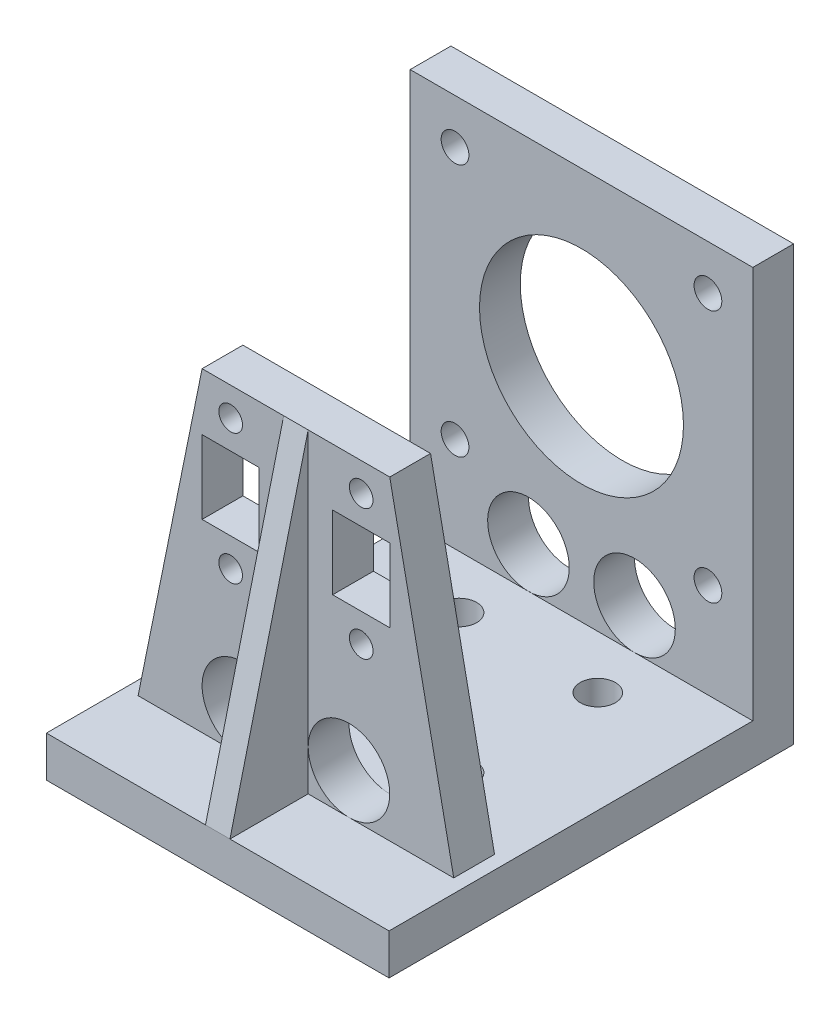
SolidWorks part; units mm, degrees
material "ABS"
ref_plane "Front Plane" through (0, 0, 0) normal (0, 0, 1) x (1, 0, 0)
ref_plane "Top Plane" through (0, 0, 0) normal (0, 1, 0) x (1, 0, 0)
ref_plane "Right Plane" through (0, 0, 0) normal (1, 0, 0) x (0, 0, -1)
sketch "Mouting Mount Sketch" plane through (0, 0, 0) normal (0, 0, 1) x (1, 0, 0)
  line L1 (25, -55) -> (-25, -55)
  line L2 (25, -55) -> (25, 0)
  line L3 (25, 0) -> (-25, 0)
  line L4 (-25, -55) -> (-25, 0)
  line L5 (25, -55) -> (-25, 0) construction
  line L6 (25, 0) -> (-25, -55) construction
  circle A0 centre (0, 0) radius 10
  point P3 (0, -27.5)
  dimension "D1" = 20
  dimension "D2" = 50
  dimension "D3" = 55
extrude "Motor Mount Solid" add sketch "Mouting Mount Sketch" along normal mid plane 15 contours A0 L3 L4 L1 L2
sketch "Encoder Distance Sketch" plane through (0, -55, 0) normal (0, -1, 0) x (1, 0, 0)
  line L0 (25, 7.5) -> (25, -7.5) construction
  line L1 (-25, 7.5) -> (25, 7.5)
  line L2 (-25, 7.5) -> (-25, 37.5)
  line L3 (-25, 37.5) -> (25, 37.5)
  line L4 (25, 7.5) -> (25, 37.5)
  line L5 (-25, -7.5) -> (25, -7.5) construction
  line L6 (-25, -7.5) -> (-25, 42.5) construction
  line L7 (-25, 42.5) -> (25, 42.5) construction
  line L8 (25, -7.5) -> (25, 42.5) construction
  line M9 (-25, -7.5) -> (25, -7.5)
  line M10 (25, -7.5) -> (25, 7.5)
  line M11 (25, 7.5) -> (-25, 7.5)
  line M12 (-25, 7.5) -> (-25, -7.5)
  dimension "D1" = 30
  dimension "D2" = 5
extrude "Encoder Distance Solid" add sketch "Encoder Distance Sketch" along normal blind 5 contours M12 M9 M10 M11 | L4 L3 L2 M11 | L3 L8 L7 L6
sketch "Encoder Mount Sketch" plane through (0, 0, 37.5) normal (0, 0, 1) x (1, 0, 0)
  line L0 (-25, -60) -> (-25, -55)
  line L1 (-8, -8) -> (8, -8) construction
  line L2 (-8, -8) -> (-8, 8) construction
  line L3 (-8, 8) -> (8, 8) construction
  line L4 (8, -8) -> (8, 8) construction
  line L5 (-8, -8) -> (8, 8) construction
  line L6 (-8, 8) -> (8, -8) construction
  line L7 (-11.5, -11.5) -> (11.5, -11.5) construction
  line L8 (-11.5, -11.5) -> (-11.5, 11.5) construction
  line L9 (-11.5, 11.5) -> (11.5, 11.5)
  line L10 (11.5, -11.5) -> (11.5, 11.5) construction
  line L11 (-11.5, -11.5) -> (11.5, 11.5) construction
  line L12 (-11.5, 11.5) -> (11.5, -11.5) construction
  line L13 (-11.5, 4.5) -> (-4.5, 4.5)
  line L14 (-11.5, 4.5) -> (-11.5, -4.5)
  line L15 (-11.5, -4.5) -> (-4.5, -4.5)
  line L16 (-4.5, 4.5) -> (-4.5, -4.5)
  line L17 (-11.5, 4.5) -> (-4.5, -4.5) construction
  line L18 (-11.5, -4.5) -> (-4.5, 4.5) construction
  line L19 (4.5, 4.5) -> (11.5, 4.5)
  line L20 (4.5, 4.5) -> (4.5, -4.5)
  line L21 (4.5, -4.5) -> (11.5, -4.5)
  line L22 (11.5, 4.5) -> (11.5, -4.5)
  line L23 (4.5, 4.5) -> (11.5, -4.5) construction
  line L24 (4.5, -4.5) -> (11.5, 4.5) construction
  line L25 (-25, -55) -> (-11.5, 11.5)
  line L26 (-25, -60) -> (25, -60)
  line L27 (25, -60) -> (25, -55)
  line L28 (25, -55) -> (11.5, 11.5)
  circle A0 centre (-8, 8) radius 1.45
  circle A1 centre (8, 8) radius 1.45
  circle A2 centre (-8, -8) radius 1.45
  circle A3 centre (8, -8) radius 1.45
  circle A4 centre (8, 8) radius 3.5 construction
  circle A5 centre (-8, 8) radius 3.5 construction
  circle A6 centre (-8, -8) radius 3.5 construction
  circle A7 centre (8, -8) radius 3.5 construction
  point P0 (0, 0)
  point P14 (0, 0)
  point P19 (-8, 0)
  point P24 (8, 0)
  dimension "D2" = 2.9
  dimension "D3" = 7
  dimension "D1" = 16
extrude "Encoder Mount Solid" add sketch "Encoder Mount Sketch" along normal blind 5
sketch "Motor Clamp Mounting Holes Sketch" plane through (0, 0, 0) normal (0, 1, 0) x (1, 0, 0)
  line L0 (-15, 0) -> (15, 0) construction
  circle A0 centre (-15, 0) radius 1.45
  circle A1 centre (15, 0) radius 1.45
  point P4 (0, 0)
  dimension "D2" = 2.9
  dimension "D1" = 30
extrude "Motor Clamp Mounting Holes Cut" cut sketch "Motor Clamp Mounting Holes Sketch" against normal through all both and the other way through all
sketch "Gusset Plate Sketch" plane through (0, 0, 42.5) normal (0, 0, 1) x (1, 0, 0)
  line L1 (-25, -55) -> (25, -55)
  line L2 (-25, -55) -> (-25, -60)
  line L3 (-25, -60) -> (25, -60)
  line L4 (25, -55) -> (25, -60)
extrude "Gusset Plate Solid" add sketch "Gusset Plate Sketch" along normal blind 16.5
sketch "Gusset Sketch" plane through (0, 0, 0) normal (1, 0, 0) x (0, 0, -1)
  line L0 (-42.5, 11.5) -> (-59, -55)
  line L1 (-59, -55) -> (-42.5, -55)
  line L2 (-42.5, -55) -> (-42.5, 11.5)
extrude "Gusset Solid" add sketch "Gusset Sketch" along normal mid plane 3
sketch "Mounting Plate Sketch" plane through (0, -55, 0) normal (0, 1, 0) x (1, 0, 0)
  line L0 (25, -7.5) -> (25, -37.5) construction
  line L1 (-25, -59) -> (25, -59)
  line L2 (-25, -59) -> (-25, 33)
  line L3 (-25, 33) -> (25, 33)
  line L4 (25, -59) -> (25, 33)
  line L5 (-19, -53) -> (19, -53) construction
  line L6 (-19, 27) -> (19, 27) construction
  circle A0 centre (-19, -53) radius 2.65
  circle A1 centre (19, -53) radius 6 construction
  circle A2 centre (19, -53) radius 2.65
  circle A3 centre (-19, -53) radius 6 construction
  circle A4 centre (-19, 27) radius 6 construction
  circle A5 centre (19, 27) radius 6 construction
  circle A6 centre (-19, 27) radius 2.65
  circle A7 centre (19, 27) radius 2.65
  point P10 (0, -53)
  point P18 (0, 27)
  dimension "D1" = 12
  dimension "D2" = 5.3
  dimension "D3" = 80
extrude "Mounting Plate Solid" add sketch "Mounting Plate Sketch" against normal up to surface (5 mm away) up to face at (-16.45, -60, 0)
sketch "Mounting Hole Sketch" plane through (0, -55, 0) normal (0, 1, 0) x (1, 0, 0)
  line L0 (25, 33) -> (25, -59) construction
  line L3 (25, -13) -> (-25, -13) construction
  line L4 (-25, -37.5) -> (-25, -7.5) construction
  circle A0 centre (-19, 27) radius 2.65
  circle A1 centre (19, 27) radius 2.65
  circle A3 centre (19, -53) radius 2.65
  circle A4 centre (-19, -53) radius 2.65
  circle A5 centre (-19, 27) radius 2.65 construction
extrude "Mounting Holes Cut" cut sketch "Mounting Hole Sketch" against normal through all both and the other way through all contours A3 | A4 | A1 | A0
sketch "Mounting Plate Trim Sketch" plane through (0, -55, 0) normal (0, 1, 0) x (1, 0, 0)
  line L1 (-25, 33) -> (25, 33)
  line L2 (-25, 33) -> (-25, 7.5)
  line L3 (-25, 7.5) -> (25, 7.5)
  line L4 (25, 33) -> (25, 7.5)
  line L5 (-25, -7.5) -> (25, -7.5)
  line L6 (-25, -7.5) -> (-25, -37.5)
  line L7 (-25, -37.5) -> (25, -37.5)
  line L8 (25, -7.5) -> (25, -37.5)
  line L9 (1.5, -42.5) -> (25, -42.5)
  line L10 (1.5, -42.5) -> (1.5, -59)
  line L11 (1.5, -59) -> (25, -59)
  line L12 (25, -42.5) -> (25, -59)
  line L13 (-1.5, -42.5) -> (-25, -42.5)
  line L14 (-1.5, -42.5) -> (-1.5, -59)
  line L15 (-1.5, -59) -> (-25, -59)
  line L16 (-25, -42.5) -> (-25, -59)
extrude "Mounting Plate Trim Cut" cut sketch "Mounting Plate Trim Sketch" against normal blind 2
sketch "Sketch2" plane through (0, 0, -7.5) normal (0, 0, -1) x (-1, 0, 0)
  line L1 (-21, -27.1363) -> (21, -27.1363)
  line L2 (-21, -27.1363) -> (-21, 27.1363)
  line L3 (-21, 27.1363) -> (21, 27.1363)
  line L4 (21, -27.1363) -> (21, 27.1363)
  line L5 (-21, -27.1363) -> (21, 27.1363) construction
  line L6 (-21, 27.1363) -> (21, -27.1363) construction
  line L7 (25, 60) -> (-25, 60)
  line L8 (25, 60) -> (25, -60)
  line L9 (25, -60) -> (-25, -60)
  line L10 (-25, 60) -> (-25, -60)
  line L11 (25, 60) -> (-25, -60) construction
  line L12 (25, -60) -> (-25, 60) construction
  point P0 (0, 0)
  point P7 (0, 0)
  dimension "D1" = 42
  dimension "D2" = 27.1363
extrude "Cut-Extrude1" cut sketch "Sketch2" against normal through all both and the other way through all
sketch "Sketch3" plane through (0, -27.1363, 0) normal (0, -1, 0) x (1, 0, 0)
  line L0 (21, 7.5) -> (21, -7.5) construction
  line L1 (-21, -7.5) -> (21, -7.5)
  line L2 (-21, -7.5) -> (-21, 52.0865)
  line L3 (-21, 52.0865) -> (21, 52.0865)
  line L4 (21, -7.5) -> (21, 52.0865)
  line L5 (-21, -7.5) -> (21, -7.5) construction
  line L6 (1.5, 52.0865) -> (-1.5, 52.0865) construction
extrude "Boss-Extrude1" add sketch "Sketch3" along normal blind 5
sketch "Sketch4" plane through (0, -27.1363, 0) normal (0, 1, 0) x (1, 0, 0)
  line L0 (21, -7.5) -> (21, -52.0865) construction
  line L1 (-21, -7.5) -> (21, -7.5) construction
  line L2 (-21, -7.5) -> (-21, -37.5) construction
  line L3 (-21, -37.5) -> (21, -37.5) construction
  line L4 (21, -7.5) -> (21, -37.5) construction
  line L5 (19.3435, -37.5) -> (-19.3435, -37.5) construction
  line L6 (-21, -7.5) -> (21, -37.5) construction
  line L8 (-8.5, -31) -> (8.5, -31) construction
  line L9 (-8.5, -31) -> (-8.5, -14) construction
  line L10 (-8.5, -14) -> (8.5, -14) construction
  line L11 (8.5, -31) -> (8.5, -14) construction
  line L12 (-8.5, -31) -> (8.5, -14) construction
  line L13 (-8.5, -14) -> (8.5, -31) construction
  circle A0 centre (8.5, -14) radius 5 construction
  circle A1 centre (-8.5, -14) radius 5 construction
  circle A2 centre (-8.5, -31) radius 5 construction
  circle A3 centre (8.5, -31) radius 5 construction
  circle A4 centre (-8.5, -14) radius 2.15
  circle A5 centre (8.5, -14) radius 2.15
  circle A6 centre (-8.5, -31) radius 2.15
  circle A7 centre (8.5, -31) radius 2.15
  point P9 (0, -22.5)
  dimension "D1" = 10
  dimension "D4" = 4.3
  dimension "D2" = 17
  dimension "D3" = 17
extrude "Cut-Extrude2" cut sketch "Sketch4" against normal through all both and the other way through all contours A5 | A4
sketch "Sketch5" plane through (0, 0, 7.5) normal (0, 0, 1) x (1, 0, 0)
  line L1 (-21, -21) -> (21, -21)
  line L2 (-21, -21) -> (-21, 21)
  line L3 (-21, 21) -> (21, 21)
  line L4 (21, -21) -> (21, 21)
  line L5 (-21, -21) -> (21, 21) construction
  line L6 (-21, 21) -> (21, -21) construction
  point P0 (0, 0)
  dimension "D1" = 42
extrude "Boss-Extrude2" add sketch "Sketch5" against normal blind 5
sketch "Sketch6" plane through (0, 0, -7.5) normal (0, 0, -1) x (-1, 0, 0)
  line L1 (-21, -32.1363) -> (21, -32.1363)
  line L2 (-21, -32.1363) -> (-21, 21)
  line L3 (-21, 21) -> (21, 21)
  line L4 (21, -32.1363) -> (21, 21)
extrude "Cut-Extrude3" cut sketch "Sketch6" against normal up to surface (10 mm away) up to face at (0, 5.3333, 2.5)
sketch "Sketch7" plane through (0, 0, 2.5) normal (0, 0, -1) x (-1, 0, 0)
  line L1 (-15.5, -15.5) -> (15.5, -15.5) construction
  line L2 (-15.5, -15.5) -> (-15.5, 15.5) construction
  line L3 (-15.5, 15.5) -> (15.5, 15.5) construction
  line L4 (15.5, -15.5) -> (15.5, 15.5) construction
  line L5 (-15.5, -15.5) -> (15.5, 15.5) construction
  line L6 (-15.5, 15.5) -> (15.5, -15.5) construction
  circle A0 centre (0, 0) radius 12.5
  circle A1 centre (-15.5, 15.5) radius 1.7
  circle A2 centre (15.5, 15.5) radius 1.7
  circle A3 centre (-15.5, -15.5) radius 1.7
  circle A4 centre (15.5, -15.5) radius 1.7
  dimension "D1" = 3.4
  dimension "D2" = 25
  dimension "D3" = 31
extrude "Cut-Extrude4" cut sketch "Sketch7" against normal up to surface (5 mm away) contours L2 L1 L4 L3
sketch "Sketch8" plane through (0, 0, 42.5) normal (0, 0, 1) x (1, 0, 0)
  line L0 (-6.5, -22.1363) -> (6.5, -22.1363) construction
  line L1 (-1.5, -27.1363) -> (-19.3435, -27.1363) construction
  line L2 (-1.5, -27.1363) -> (-1.5, 11.5) construction
  circle A0 centre (-6.5, -22.1363) radius 5
  circle A1 centre (6.5, -22.1363) radius 5
  point P3 (0, -22.1363)
  point P9 (0, 0)
  point P10 (0, 0)
  dimension "D1" = 10
extrude "Cut-Extrude5" cut sketch "Sketch8" against normal through all
